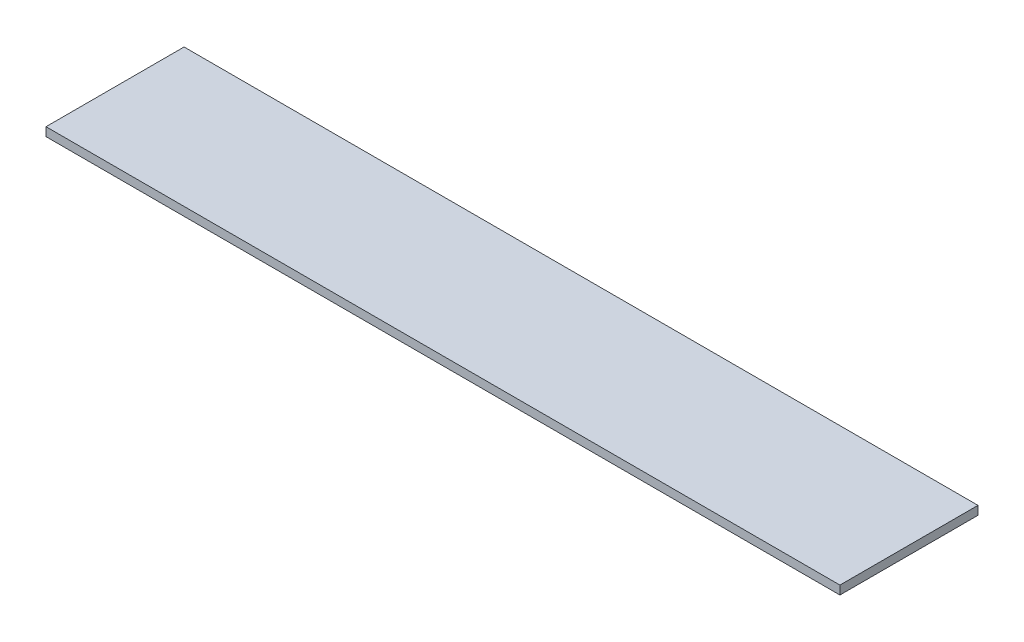
SolidWorks part; units mm, degrees
material "6061 Alloy"
ref_plane "Front Plane" through (0, 0, 0) normal (0, 0, 1) x (1, 0, 0)
ref_plane "Top Plane" through (0, 0, 0) normal (0, 1, 0) x (1, 0, 0)
ref_plane "Right Plane" through (0, 0, 0) normal (1, 0, 0) x (0, 0, -1)
sketch "Sketch1" plane through (0, 0, 0) normal (0, 1, 0) x (1, 0, 0)
  line L1 (0, 0) -> (292.1, 0)
  line L2 (0, 0) -> (0, -50.8)
  line L3 (0, -50.8) -> (292.1, -50.8)
  line L4 (292.1, 0) -> (292.1, -50.8)
  dimension "D1" = 292.1
  dimension "D2" = 50.8
extrude "Boss-Extrude1" add sketch "Sketch1" along normal blind 3.175
